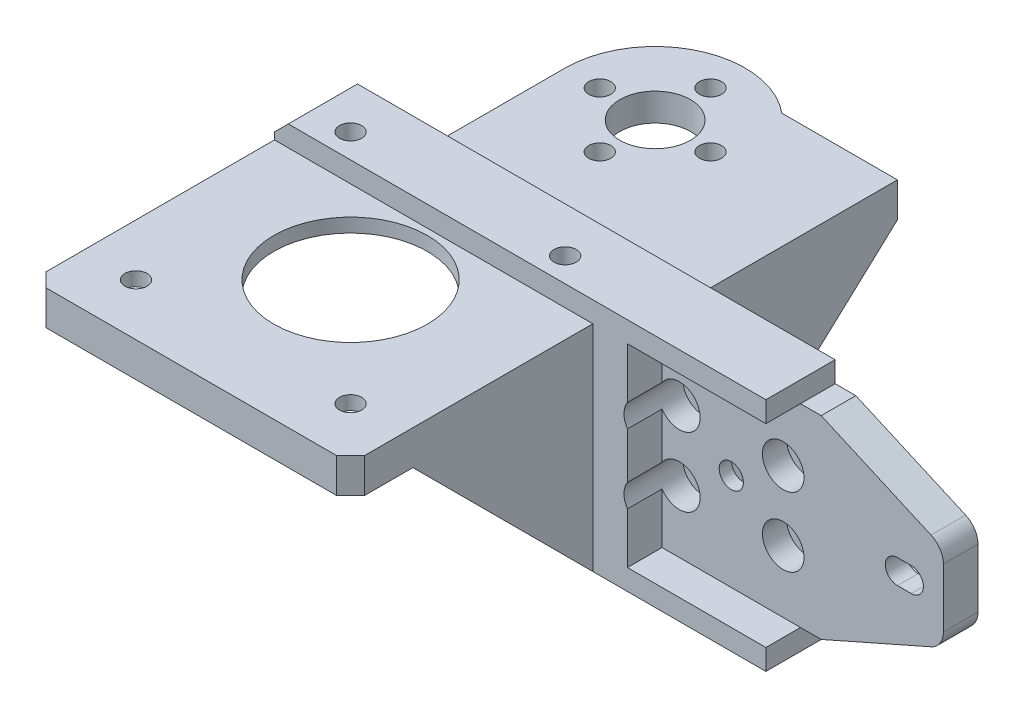
SolidWorks part; units mm, degrees
material "自定义塑料"
ref_plane "前视基准面" through (0, 0, 0) normal (0, 0, 1) x (1, 0, 0)
ref_plane "上视基准面" through (0, 0, 0) normal (0, 1, 0) x (1, 0, 0)
ref_plane "右视基准面" through (0, 0, 0) normal (1, 0, 0) x (0, 0, -1)
sketch "草图1" plane through (0, 0, 0) normal (0, 0, 1) x (1, 0, 0)
  line L1 (0, 0) -> (-20, 0)
  line L2 (0, 0) -> (0, 34)
  line L3 (0, 34) -> (-20, 34)
  line L4 (-20, 0) -> (-20, 34)
  dimension "D1" = 34
  dimension "D2" = 20
extrude "凸台-拉伸1" add sketch "草图1" along normal blind 5
sketch "草图2" plane through (0, 0, 5) normal (0, 0, 1) x (1, 0, 0)
  line L0 (0, 0) -> (0, 34) construction
  line L1 (-20, 34) -> (0, 34)
  line L2 (-20, 34) -> (-20, 31)
  line L3 (-20, 31) -> (0, 31)
  line L4 (0, 34) -> (0, 31)
  line L6 (-20, 0) -> (0, 0)
  line L7 (-20, 0) -> (-20, 3)
  line L8 (-20, 3) -> (0, 3)
  line L9 (0, 0) -> (0, 3)
  dimension "D1" = 3
  dimension "D2" = 3
extrude "凸台-拉伸2" add sketch "草图2" along normal blind 5
sketch "草图4" plane through (0, 0, 0) normal (0, 0, -1) x (-1, 0, 0)
  line L0 (-1047.5681, 17) -> (-20.6407, 17) construction
  line L1 (0, 0) -> (0, 34) construction
  line L2 (20, 34) -> (20, 0) construction
  line L3 (0, 31) -> (-2.9917, 31)
  line L4 (-2.9917, 31) -> (-20.6407, 23.2036)
  line L5 (-20.6407, 23.2036) -> (-20.6407, 10.7964)
  line L6 (0, 3) -> (-2.9917, 3)
  line L7 (-2.9917, 3) -> (-20.6407, 10.7964)
  line L8 (0, 31) -> (0, 3)
  line L9 (0, 31) -> (0, 3)
  line L10 (-16, 18.75) -> (-14, 18.75)
  line L11 (-16, 15.25) -> (-14, 15.25)
  line L14 (0, 17) -> (50000, 17) construction
  arc A0 (-16, 18.75) -> (-16, 15.25) centre (-16, 17) ccw
  arc A1 (-14, 15.25) -> (-14, 18.75) centre (-14, 17) ccw
  point P4 (0, 17)
  point P7 (20, 17)
  point P19 (-20.6407, 17)
  line M1 (0, 34) -> (0, 0)
  dimension "D1" = 3.5
  dimension "D2" = 3.5
  dimension "D3" = 2
  dimension "D4" = 14
  dimension "D5" = 28
extrude "凸台-拉伸3" add sketch "草图4" against normal blind 5 contours L7 L6 L3 L4 L5 A1 L11 A0 L10 M1
fillet "圆角1" radius 3 2 edges at (20.6407, 23.2036, 2.5) (20.6407, 10.7964, 2.5)
sketch "草图5" plane through (0, 0, 0) normal (0, 0, -1) x (-1, 0, 0)
  line L0 (-16, 20.25) -> (-13.5058, 20.2122)
  line L1 (-16, 13.75) -> (-14, 13.75)
  arc A0 (-16, 20.25) -> (-16, 13.75) centre (-16, 17) ccw
  arc A1 (-14, 13.75) -> (-13.5058, 20.2122) centre (-14, 17) ccw
  dimension "D1" = 6.5
  dimension "D2" = 6.5
extrude "切除-拉伸1" cut sketch "草图5" against normal blind 2
sketch "草图7" plane through (0, 0, 5) normal (0, 0, 1) x (1, 0, 0)
  line L0 (-20, 17) -> (20.6407, 17) construction
  line L1 (-20, 31) -> (-20, 3) construction
  line L2 (20.6407, 21.2491) -> (20.6407, 12.7509) construction
  line L3 (-10, 34) -> (-10, 0) construction
  line L4 (0, 34) -> (-20, 34) construction
  line L5 (-20, 0) -> (0, 0) construction
  circle A0 centre (-17.5, 22) radius 1.6
  circle A1 centre (-2.5, 22) radius 1.6
  circle A2 centre (-2.5, 12) radius 1.6
  circle A3 centre (-17.5, 12) radius 1.6
  dimension "D1" = 3.2
  dimension "D2" = 10
  dimension "D3" = 15
extrude "切除-拉伸2" cut sketch "草图7" against normal through all
sketch "草图8" plane through (0, 0, 5) normal (0, 0, 1) x (1, 0, 0)
  line L0 (-10, 3) -> (-10, 31) construction
  line L1 (0, 3) -> (-20, 3) construction
  line L2 (-20, 31) -> (0, 31) construction
  line L3 (-20, 17) -> (-10, 17) construction
  line L4 (-20, 31) -> (-20, 3) construction
  circle A0 centre (-10, 17) radius 1.75
  dimension "D1" = 3.5
extrude "切除-拉伸3" cut sketch "草图8" against normal through all
sketch "草图9" plane through (0, 0, 0) normal (0, 0, -1) x (-1, 0, 0)
  line L1 (11.6688, 13.9643) -> (13.4633, 16.9274)
  line L2 (13.4633, 16.9274) -> (11.7946, 19.963)
  line L3 (11.7946, 19.963) -> (8.3312, 20.0357)
  line L4 (8.3312, 20.0357) -> (6.5367, 17.0726)
  line L5 (6.5367, 17.0726) -> (8.2054, 14.037)
  line L6 (8.2054, 14.037) -> (11.6688, 13.9643)
  circle A0 centre (10, 17) radius 3 construction
  dimension "D1" = 6
extrude "切除-拉伸5" cut sketch "草图9" against normal blind 3.2
sketch "草图11" plane through (0, 31, 0) normal (0, -1, 0) x (1, 0, 0)
  line L0 (-20, 10) -> (-20, 5) construction
  line L1 (-20, -42.153) -> (-71, -42.153)
  line L2 (-20, -42.153) -> (-20, 45)
  line L3 (-20, 45) -> (-71, 45)
  line L4 (-71, -42.153) -> (-71, 45)
  line L5 (-18.0411, 5) -> (49035.5694, 5) construction
  line L7 (-48, 25.9659) -> (-48, 8.9659) construction
  line L8 (-42.6338, 22) -> (49957.3662, 22) construction
  line L9 (-20, 5) -> (0, 5) construction
  circle A0 centre (-48, 22) radius 11.1
  circle A1 centre (-32.5, 37.5) radius 1.6
  circle A2 centre (-32.5, 6.5) radius 1.6
  circle A3 centre (-63.5, 6.5) radius 1.6
  circle A4 centre (-63.5, 37.5) radius 1.6
  dimension "D2" = 22.2
  dimension "D3" = 3.2
  dimension "D1" = 17
  dimension "D4" = 31
  dimension "D5" = 31
  dimension "D6" = 28
  dimension "D7" = 23
  dimension "D8" = 23
sketch "草图14" plane through (-20, 0, 0) normal (-1, 0, 0) x (0, 0, 1)
  line L1 (0, 34) -> (10, 34)
  line L2 (0, 34) -> (0, 31)
  line L3 (0, 31) -> (10, 31)
  line L4 (10, 34) -> (10, 31)
extrude "凸台-拉伸26" add sketch "草图14" along normal up to vertex (51 mm away) up to point (-71, 31, 45)
extrude "凸台-拉伸27" add sketch "草图11" along normal blind 5
sketch "草图15" plane through (0, 26, 0) normal (0, -1, 0) x (1, 0, 0)
  line L0 (-48, 22) -> (-20, 22) construction
  line L1 (-67.3, 43.3) -> (-28.7, 43.3)
  line L2 (-69.3, 41.3) -> (-69.3, 2.7)
  line L3 (-67.3, 0.7) -> (-28.7, 0.7)
  line L4 (-26.7, 41.3) -> (-26.7, 2.7)
  line L6 (-48, 22) -> (-48, -42.153) construction
  line L7 (-71, -42.153) -> (-20, -42.153) construction
  line L8 (-28.7, 0.7) -> (-26.7, 2.7)
  line L9 (-69.3, 2.7) -> (-67.3, 0.7)
  line L10 (-69.3, 41.3) -> (-67.3, 43.3)
  line L11 (-28.7, 43.3) -> (-26.7, 41.3)
  point P0 (-69.3, 43.3)
  point P1 (-26.7, 0.7)
  point P2 (-69.3, 0.7)
  point P3 (-26.7, 43.3)
  dimension "D1" = 42.6
  dimension "D2" = 42.6
extrude "切除-拉伸7" cut sketch "草图15" against normal blind 3
sketch "草图16" plane through (0, 29, 0) normal (0, -1, 0) x (1, 0, 0)
  circle A0 centre (-63.5, 6.5) radius 1.6
  circle A1 centre (-32.5, 6.5) radius 1.6
extrude "切除-拉伸8" cut sketch "草图16" against normal through all
sketch "草图17" plane through (-20, 0, 0) normal (-1, 0, 0) x (0, 0, 1)
  line L0 (0, 26) -> (5, 26)
  line L1 (5, 26) -> (5, 3)
  line L2 (5, 3) -> (10, 3)
  line L3 (10, 3) -> (10, 0)
  line L4 (10, 0) -> (0, 0)
  line L5 (0, 0) -> (0, 26)
extrude "凸台-拉伸28" add sketch "草图17" along normal up to surface (6.7 mm away) up to face at (-26.7, 27.5, 22)
sketch "草图18" plane through (-20, 0, 0) normal (1, 0, 0) x (0, 0, -1)
  line L1 (-5, 31) -> (-45, 31)
  line L2 (-5, 31) -> (-5, 26)
  line L3 (-5, 26) -> (-45, 26)
  line L4 (-45, 31) -> (-45, 26)
extrude "切除-拉伸9" cut sketch "草图18" against normal blind 5
chamfer "倒角1" distance 2 angle 45 3 edges at (-71, 28.5, 45) (-25, 28.5, 45) (-71, 34, 5)
sketch "草图19" plane through (0, 0, 5) normal (0, 0, 1) x (1, 0, 0)
  line L0 (-25, 26) -> (-25, 31) construction
  line L1 (-26.7, 3) -> (-25, 3)
  line L2 (-26.7, 3) -> (-26.7, 26)
  line L3 (-26.7, 26) -> (-25, 26)
  line L4 (-25, 3) -> (-25, 26)
extrude "凸台-拉伸31" add sketch "草图19" along normal up to vertex
sketch "草图20" plane through (-25, 0, 0) normal (1, 0, 0) x (0, 0, -1)
  line L1 (-10, 3) -> (-5, 3)
  line L2 (-10, 3) -> (-10, 31)
  line L3 (-10, 31) -> (-5, 31)
  line L4 (-5, 3) -> (-5, 31)
extrude "凸台-拉伸33" add sketch "草图20" along normal blind 5
sketch "草图23" plane through (-25, 0, 0) normal (1, 0, 0) x (0, 0, -1)
  line L0 (-10, 0) -> (-10, 26)
  line L1 (-10, 26) -> (-36, 26)
  line L2 (-43, 26) -> (-10, 26) construction
  line L3 (-36, 26) -> (-10, 0)
  dimension "D1" = 26
extrude "凸台-拉伸34" add sketch "草图23" against normal up to surface (1.7 mm away) up to face at (-26.7, 20.25, 13.5)
sketch "草图24" plane through (0, 26, 0) normal (0, -1, 0) x (1, 0, 0)
  line L0 (-48, 22) -> (-48, -49978) construction
  line L1 (-20, -42.153) -> (-20, 0) construction
  circle A0 centre (-46, -20) radius 11.1
  dimension "D1" = 22.2
  dimension "D2" = 26
  dimension "D3" = 20
extrude "切除-拉伸10" cut sketch "草图24" against normal blind 1
sketch "草图25" plane through (0, 26, 0) normal (0, -1, 0) x (1, 0, 0)
  line L0 (-78.5191, -1.3) -> (-59, -1.3)
  line L1 (-59, -1.3) -> (-59, -20)
  line L3 (-21, -30) -> (-21, 0)
  line L4 (-26.7, 0) -> (0, 0) construction
  line L5 (-21, 0) -> (-16.8876, 0)
  line L6 (-16.8876, 0) -> (-16.8876, -53.6806)
  line L7 (-16.8876, -53.6806) -> (-78.5191, -54.7852)
  line L8 (-78.5191, -54.7852) -> (-78.5191, -1.3)
  line L9 (-67.3, 0.7) -> (-28.7, 0.7) construction
  line L10 (-20, -42.153) -> (-20, 0) construction
  line L11 (-21, -30) -> (-37.6934, -30)
  arc A0 (-59, -20) -> (-37.6934, -30) centre (-46, -20) ccw
  dimension "D3" = 26
  dimension "D1" = 2
  dimension "D2" = 1
  dimension "D4" = 30
extrude "切除-拉伸12" cut sketch "草图25" against normal through all
sketch "草图26" plane through (0, 27, 0) normal (0, -1, 0) x (1, 0, 0)
  circle A0 centre (-46, -20) radius 5.1
  dimension "D1" = 10.2
extrude "切除-拉伸13" cut sketch "草图26" against normal through all
chamfer "倒角2" distance 2 angle 45 1 edges at (-71, 28.5, -1.3)
sketch "草图27" plane through (-26.7, 0, 0) normal (-1, 0, 0) x (0, 0, 1)
  line L0 (0, 0) -> (0, 26)
  line L1 (0, 0) -> (-1.722, 0)
  line L2 (-30, 26) -> (0, 26)
  line L3 (-30, 31) -> (-30, 26) construction
  line L4 (-1.722, 0) -> (-30, 26)
  line L5 (10, 0) -> (0, 0) construction
extrude "凸台-拉伸35" add sketch "草图27" against normal up to surface (5.7 mm away) up to face at (-21, 28.5, -15)
sketch "草图28" plane through (0, 0, 0.7) normal (0, 0, 1) x (1, 0, 0)
  line L0 (-55.0791, 26) -> (-26.7, 26)
  line L1 (-67.3, 26) -> (-28.7, 26) construction
  line L2 (-26.7, 26) -> (-26.7, 0)
  line L3 (-26.7, 0) -> (-55.0791, 26)
  line L4 (-20, 31) -> (-20, 3) construction
extrude "凸台-拉伸36" add sketch "草图28" against normal blind 2
sketch "草图29" plane through (0, 26, 0) normal (0, -1, 0) x (1, 0, 0)
  line L0 (-26.7, 2.7) -> (-28.7, 0.7)
  line L1 (-28.7, 0.7) -> (-26.7, 0.7)
  line L2 (-26.7, 0.7) -> (-26.7, 2.7)
extrude "凸台-拉伸37" add sketch "草图29" along normal up to vertex (26 mm away)
sketch "草图30" plane through (0, 0, 0.7) normal (0, 0, -1) x (-1, 0, 0)
  line L0 (28.7, 0) -> (26.7, 0)
  line L1 (26.7, 0) -> (28.7, 1.8323)
  line L2 (28.7, 1.8323) -> (26.7, 0) construction
  line L3 (28.7, 0) -> (28.7, 1.8323) construction
  line L4 (28.7, 1.8323) -> (28.7, 0)
extrude "切除-拉伸14" cut sketch "草图30" against normal through all
sketch "草图32" plane through (0, 27, 0) normal (0, -1, 0) x (1, 0, 0)
  line L0 (-46, -20) -> (-46, 49980) construction
  line L1 (-43, -20) -> (49957, -20) construction
  circle A0 centre (-46, -12) radius 1.6
  circle A1 centre (-54, -20) radius 1.6
  circle A2 centre (-38, -20) radius 1.6
  circle A3 centre (-46, -28) radius 1.6
  point P16 (-44.5, -21.5)
  point P17 (-46, -20)
  dimension "D1" = 3.2
  dimension "D3" = 4
  dimension "D2" = 8
extrude "切除-拉伸15" cut sketch "草图32" against normal through all
sketch "草图33" plane through (0, 0, 5) normal (0, 0, 1) x (1, 0, 0)
  circle A0 centre (-2.5, 12) radius 3
  circle A1 centre (-17.5, 12) radius 3
  circle A2 centre (-2.5, 22) radius 3
  circle A3 centre (-17.5, 22) radius 3
  dimension "D1" = 6
  dimension "D2" = 6
  dimension "D3" = 6
  dimension "D4" = 6
extrude "切除-拉伸16" cut sketch "草图33" against normal blind 3.5 and the other way blind 10
